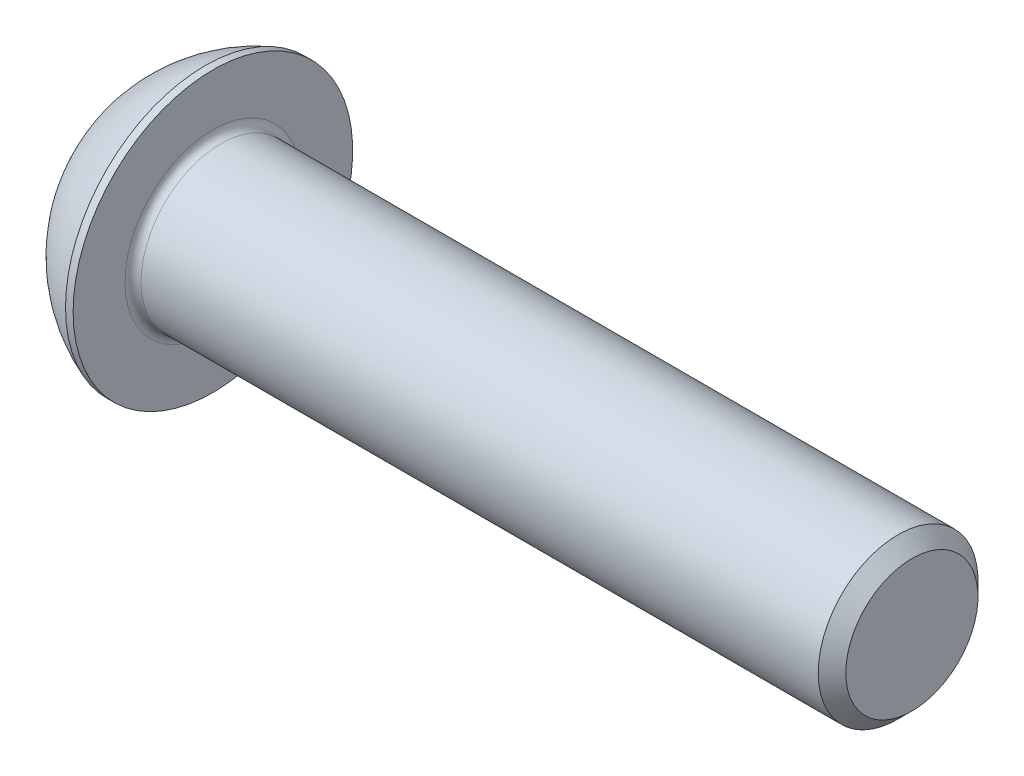
SolidWorks part; units mm, degrees
ref_plane "Plane1" through (0, 0, 0) normal (0, 0, 1) x (1, 0, 0)
ref_plane "Plane2" through (0, 0, 0) normal (0, 1, 0) x (1, 0, 0)
ref_plane "Plane3" through (0, 0, 0) normal (1, 0, 0) x (0, 0, -1)
sketch "BodySke" plane through (0, 0, 0) normal (0, 0, 1) x (1, 0, 0)
  line L0 (39.4, 0) -> (39.4, 3.3095)
  line L1 (38.7095, 4) -> (4.4, 4)
  line L2 (4.4, 4) -> (4.4, 7)
  line L3 (4.4, 7) -> (4.02, 7)
  line L4 (0, 0) -> (101.6, 0) construction
  line L5 (4.4, -7) -> (4.02, -7) construction
  line L6 (55.6768, -4) -> (4.4, -4) construction
  line L7 (39.4, 0) -> (0, 0)
  line L8 (0, 3.5) -> (0, -3.5) construction
  line L9 (0, 0) -> (0, 3.5)
  line L10 (39.4, 3.3095) -> (38.7095, 4)
  line L11 (39.4, -3.3095) -> (38.7095, -4) construction
  line L12 (5.65, 9.525) -> (5.65, -4) construction
  line L13 (4.4, 9.525) -> (4.4, -4) construction
  arc A1 (0, 3.5) -> (4.02, 7) centre (6.5809, 0) cw
  dimension "Head_side_ht" = 0.38
  dimension "Body_ch_ang" = 45
revolve "BaseBody" add sketch "BodySke" angle 360 about L4
cosmetic thread "ThreadCosmetic" [suppressed] parameters "Thread_length"=32.5, "Thread_minor"=6.619
fillet "Fillet1" radius 0.4 1 edges at (4.4, 0, 4)
sketch "Sketch2" plane through (0, 0, 0) normal (0, 0, 1) x (1, 0, 0)
  line L0 (0, 2.5) -> (2.6, 2.5)
  line L1 (2.6, 2.5) -> (4.0434, 0)
  line L3 (4.0434, 0) -> (0, 0)
  line L4 (0, 0) -> (0, 2.5)
  line L5 (0, -2.5) -> (2.6, -2.5) construction
  line L6 (0, 0) -> (47.625, 0) construction
  dimension "D2" = 60
  dimension "PreBroach_depth" = 2.6
  dimension "PreBroach_dia" = 5
revolve "PreBroach" cut sketch "Sketch2" angle 360 about L6
sketch "Sketch3" plane through (0, 0, 0) normal (1, 0, 0) x (0, 0, -1)
  line L0 (-2.5, -1.4434) -> (-2.5, 1.4434)
  line L1 (-2.5, 1.4434) -> (0, 2.8868)
  line L2 (0, 2.8868) -> (2.5, 1.4434)
  line L3 (2.5, 1.4434) -> (2.5, -1.4434)
  line L4 (2.5, -1.4434) -> (0, -2.8868)
  line L5 (0, -2.8868) -> (-2.5, -1.4434)
extrude "Hex" cut sketch "Sketch3" along normal blind 2.6
sketch "ThdSchSke" plane through (0, 0, 0) normal (0, 0, 1) x (1, 0, 0)
  line L0 (6.9, -3.3095) -> (6.4165, -4)
  line L1 (6.9, -3.3095) -> (7.3835, -4)
  line L2 (7.3835, -4) -> (7.3835, -5)
  line L3 (-3.175, 0) -> (5.1513, 0) construction
  line L5 (7.3835, -5) -> (6.4165, -5)
  line L6 (6.4165, -5) -> (6.4165, -4)
  dimension "SideAngle" = 55
  dimension "VeeAngle" = 70
revolve "ThreadSchematic" [suppressed] cut sketch "ThdSchSke" angle 360 about L3
pattern_linear "ThdSchPat" [suppressed]
equation "\"D1@BodySke\" = \"Head_dia@BodySke\" * .5"
equation "\"Thread_minor@ThreadCosmetic\" = \"Minor_dia@BodySke\""
equation "\"D1@Sketch3\" = \"Hex_size@Sketch3\" / 2"
equation "\"D2@Sketch3\" = \"D1@Sketch3\""
equation "\"D3@Sketch3\" = \"Hex_size@Sketch3\""
equation "\"Thread_length@ThreadCosmetic\" = ((sgn( (\"Length@BodySke\" - \"Advance@BodySke\" * 2.0) - \"Thread_nom@BodySke\" )-1)*( (\"Length@BodySke\" - \"Advance@BodySke\" * 2.0) - \"Thread_nom@BodySke\" ))/-2+ \"Thread_nom@BodySke\""
equation "\"Thread_minor@ThdSchSke\" = \"Minor_dia@BodySke\""
equation "\"Diameter@ThdSchSke\" = \"Diameter@BodySke\""
equation "\"Overcut@ThdSchSke\" = \"Diameter@BodySke\" * 1.25"
equation "\"Start@ThdSchSke\" = \"Head_ht@BodySke\" + \"Length@BodySke\" - \"Thread_length@ThreadCosmetic\"  '---Non-countersunk---"
equation "\"Num_threads@ThdSchPat\" = int( \"Thread_length@ThreadCosmetic\" / \"Advance@BodySke\" + 0.999 )  + 1"
equation "\"Advance@ThdSchPat\" = \"Thread_length@ThreadCosmetic\" /  (\"Num_threads@ThdSchPat\" - 1) 'relax it"
equation "\"Num_threads@ThdSchPat\" = \"Num_threads@ThdSchPat\" - sgn( \"Num_threads@ThdSchPat\" - 1) '---chamfered tips only---"
